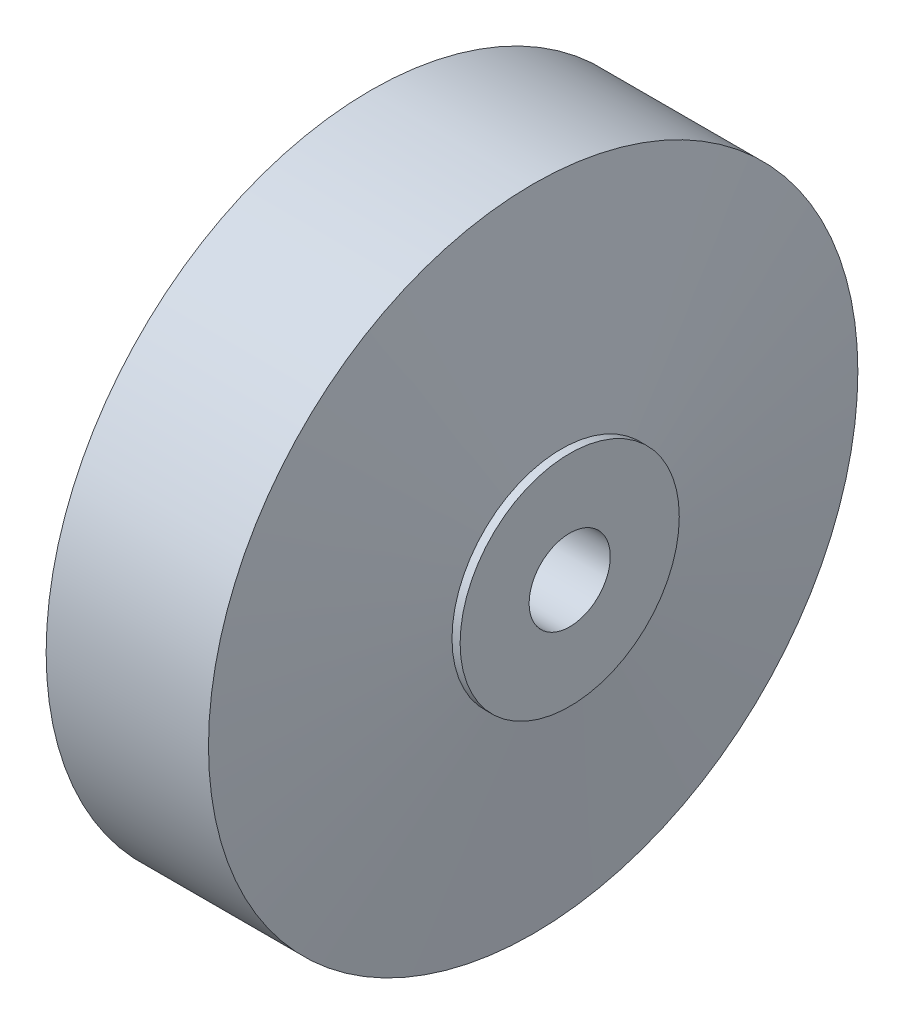
SolidWorks part; units mm, degrees
ref_plane "Front" through (0, 0, 0) normal (0, 0, 1) x (1, 0, 0)
ref_plane "Top" through (0, 0, 0) normal (0, 1, 0) x (1, 0, 0)
ref_plane "Right" through (0, 0, 0) normal (1, 0, 0) x (0, 0, -1)
sketch "Esquisse1" plane through (0, 0, 0) normal (0, 0, 1) x (1, 0, 0)
  line L0 (0, 0) -> (0, 80) construction
  line L1 (-20, 80) -> (20, 80)
  line L2 (20, 80) -> (27, 27)
  line L3 (27, 27) -> (29, 27)
  line L4 (29, 27) -> (29, 10)
  line L5 (29, 10) -> (-29, 10)
  line L6 (0, 0) -> (29, 0) construction
  line L7 (-29, 27) -> (-29, 10)
  line L8 (-27, 27) -> (-29, 27)
  line L9 (-20, 80) -> (-27, 27)
  point P10 (0, 10)
  point P13 (-29, 60.9386)
  point P14 (-26.4876, 28.4555)
  point P15 (25.6813, 27)
  dimension "D1" = 58
  dimension "D2" = 160
  dimension "D3" = 40
  dimension "D4" = 54
  dimension "D5" = 20
  dimension "D6" = 54
revolve "Révolution1" add sketch "Esquisse1" angle 360 about L6
